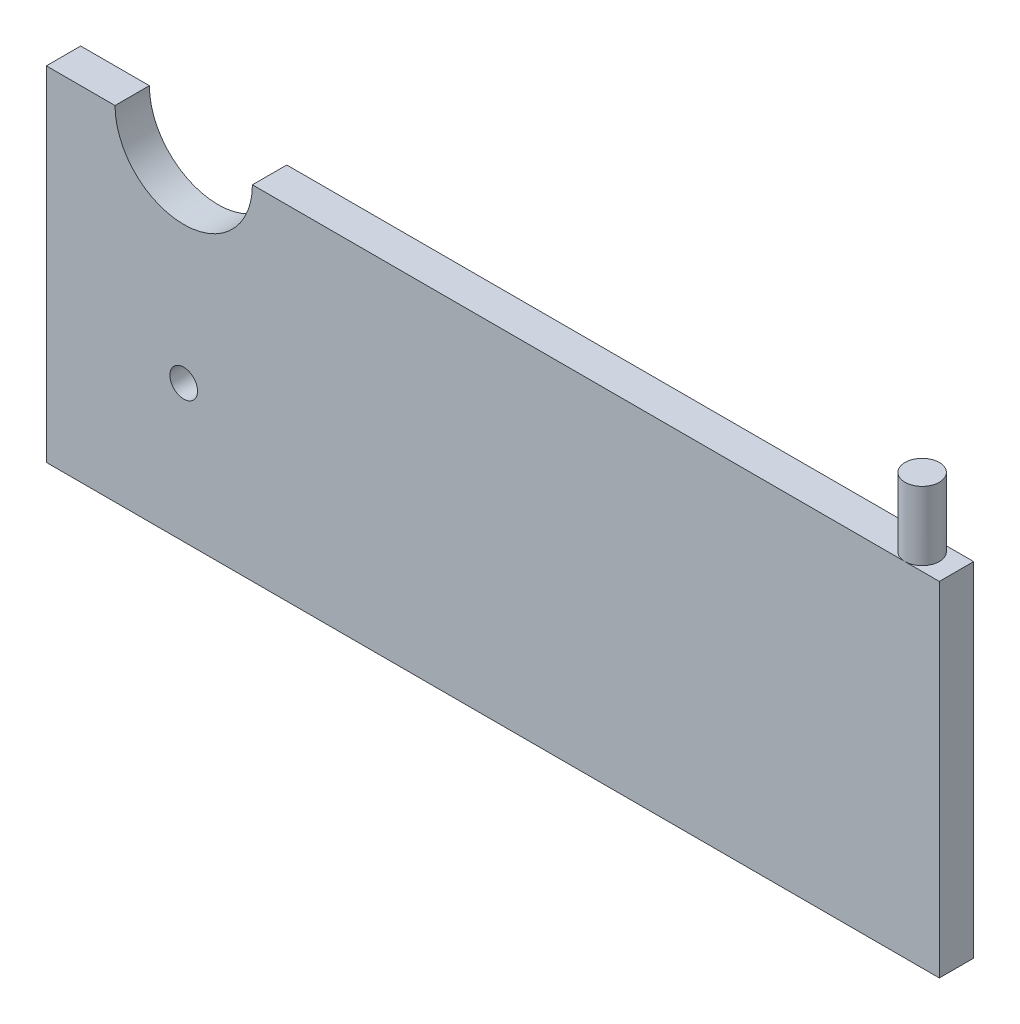
SolidWorks part; units mm, degrees
ref_plane "Front Plane" through (0, 0, 0) normal (0, 0, 1) x (1, 0, 0)
ref_plane "Top Plane" through (0, 0, 0) normal (0, 1, 0) x (1, 0, 0)
ref_plane "Right Plane" through (0, 0, 0) normal (1, 0, 0) x (0, 0, -1)
sketch "Sketch1" plane through (0, 0, 0) normal (0, 0, 1) x (1, 0, 0)
  line L1 (-25.4, 25.4) -> (-12.7, 25.4)
  line L2 (-25.4, 25.4) -> (-25.4, -38.1)
  line L3 (-25.4, -38.1) -> (139.7, -38.1)
  line L4 (139.7, 25.4) -> (139.7, -38.1)
  line L5 (12.7, 25.4) -> (139.7, 25.4)
  arc A0 (-12.7, 25.4) -> (12.7, 25.4) centre (0, 25.4) ccw
  dimension "D3" = 165.1
  dimension "D5" = 12.7
  dimension "D1" = 25.4
  dimension "D2" = 25.4
  dimension "D4" = 63.5
  dimension "D6" = 25.4
extrude "Boss-Extrude1" add sketch "Sketch1" along normal mid plane 6.35
hole_wizard "1/4-20 Tapped Hole1" positions "Sketch2" profile "Sketch3" tap size "1/4-20" standard "ANSI Inch" end condition through all
sketch "Sketch2" plane through (0, 0, 3.175) normal (0, 0, 1) x (1, 0, 0)
  point P0 (0, -12.7)
sketch "Sketch3" plane through (0, -12.7, 3.175) normal (1, 0, 0) x (0, -1, 0)
  line L0 (0, 0) -> (0, 6.35)
  line L1 (0, 6.35) -> (2.5527, 6.35)
  line L2 (2.5527, 6.35) -> (2.5527, 0)
  line L5 (2.5527, 0) -> (0, 0)
  line L11 (0, -6.35) -> (0, 107.95) construction
  dimension "Thru Tap Drill Dia." = 5.1054
  dimension "Thru Tap Drill Depth" = 6.35
cosmetic thread "Hole Thread1" parameters "D2"=6.35
sketch "Sketch4" plane through (0, 25.4, 0) normal (0, 1, 0) x (1, 0, 0)
  line L0 (-55, 0) -> (55, 0) construction
  line L2 (139.7, 3.175) -> (12.7, 3.175) construction
  line L3 (139.7, -3.175) -> (139.7, 3.175) construction
  circle A0 centre (133.35, 0) radius 3.175
  dimension "D2" = 6.35
  dimension "D1" = 6.35
extrude "Boss-Extrude2" add sketch "Sketch4" along normal blind 12.7
